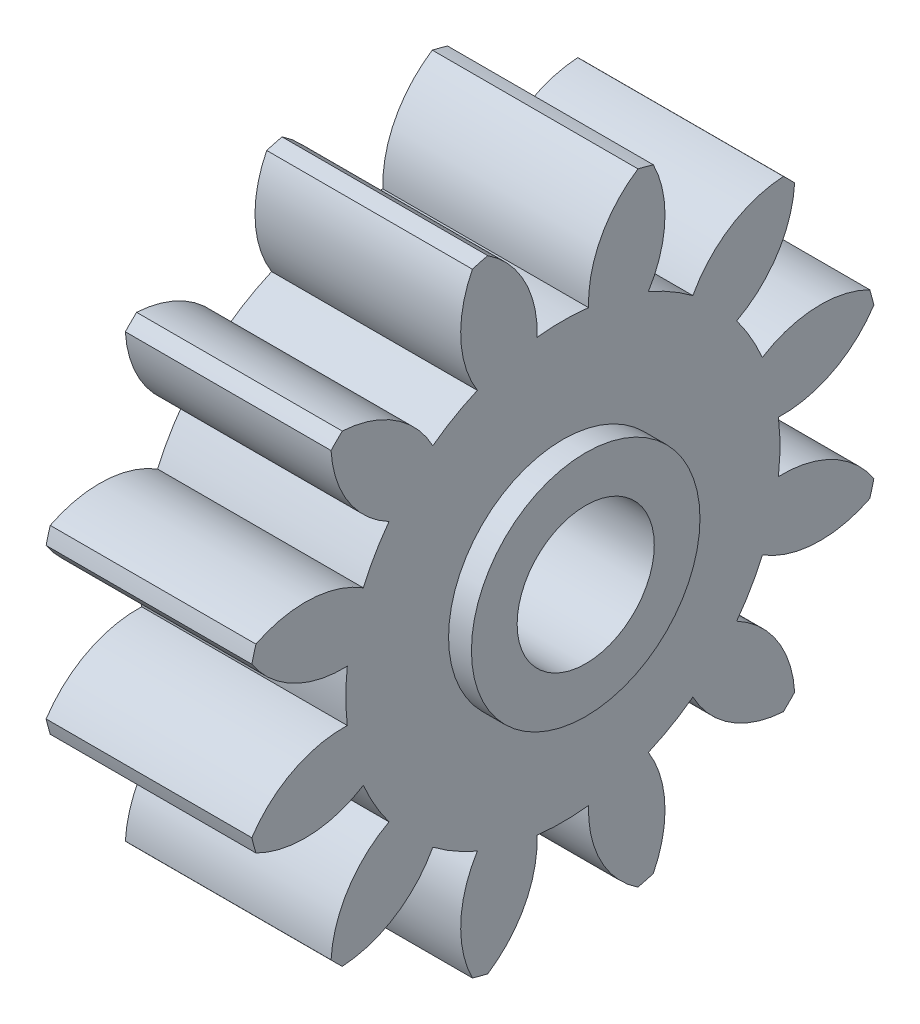
SolidWorks part; units mm, degrees
ref_plane "Plane1" through (0, 0, 0) normal (0, 0, 1) x (1, 0, 0)
ref_plane "Plane2" through (0, 0, 0) normal (0, 1, 0) x (1, 0, 0)
ref_plane "Plane3" through (0, 0, 0) normal (1, 0, 0) x (0, 0, -1)
sketch "HoldingSke" plane through (0, 0, 0) normal (0, 1, 0) x (1, 0, 0)
  line L0 (0, 0) -> (0.9781, -0.2079)
  line L1 (-15, 0) -> (100, 0) construction
  line L2 (0, 0) -> (-2.1039, 2.3779)
  line L3 (0, 0) -> (-11.863, 4.5341)
  line L4 (0, 0) -> (8.4473, 1.7955)
  line L5 (0, 0) -> (-5.1532, -1.922)
  line L6 (0, 0) -> (-3.7303, -2.5169)
  line L7 (-2.1039, 2.3779) -> (-0.92, 7.749)
  line L8 (-76.2, 54.61) -> (-75.7, 54.61)
  line L9 (-71.009, 38.7566) -> (-53.1078, 45.2721)
  line L10 (-76.2, 71.12) -> (104.1128, 71.12)
  line L11 (0, 0) -> (-4.5, 0)
  line L12 (-76.2, 101.6) -> (-76.162, 101.6)
  line L13 (24.9733, 27.94) -> (52.9518, 28.4284)
  line L14 (24.9733, 27.94) -> (24.9743, 27.94)
  line L15 (24.9733, 27.94) -> (100.4006, 29.5858)
  line L16 (-63.627, -1) -> (-12.827, -1)
  circle A0 centre (0, 0) radius 1.5
  circle A1 centre (0, 0) radius 2.5
  circle A2 centre (0, 0) radius 2.5
  circle A3 centre (0, 0) radius 1.5
  dimension "MHD" = 5
  dimension "Hub_dia" = 5
  dimension "Bore" = 3
  dimension "MBD" = 3
  dimension "Num_teeth" = 12
  dimension "Pitch" = 1
  dimension "Overall_len" = 5.5
  dimension "Show_teeth" = 12
  dimension "Thickness" = 4.5
  dimension "OAL" = 5.5001
  dimension "T_dim" = 0.5
  dimension "Ap" = 20
  dimension "H" = 19.05
  dimension "Pitch_radius" = 180.3128
  dimension "Width" = 4.5
  dimension "Backlash" = 0.038
  dimension "Addendum_fac" = 1
  dimension "Dedendum_fac" = 1.25
  dimension "Clearance_fac" = 0.25
  dimension "Dedendum_add" = 0.001
  dimension "Module" = 1
sketch "BasProSke" plane through (0, 0, 0) normal (0, 1, 0) x (1, 0, 0)
  line L0 (-10, 0) -> (60, 0) construction
  line L1 (0, 0) -> (0, 7)
  line L2 (0, 0) -> (4.5, 0)
  line L3 (4.5, 0) -> (4.5, 7)
  line L4 (4.5, 7) -> (0, 7)
  dimension "Thickness" = 4.5
  dimension "Diameter" = 14
revolve "Base-Revolve" add sketch "BasProSke" angle 360 about L0
sketch "TooCutSke" plane through (0, 0, 0) normal (1, 0, 0) x (0, 0, -1)
  line L1 (0, 0) -> (0, 107) construction
  line L2 (0, 0) -> (-0.8496, 5.9395) construction
  line L3 (0, 0) -> (-3.0836, 11.5081) construction
  line L4 (-0.8496, 5.9395) -> (-1.5418, 5.7541) construction
  arc A0 (0.5622, 4.7156) -> (-0.5622, 4.7156) centre (0, 0) ccw
  arc A1 (1.6729, 6.8233) -> (-1.6729, 6.8233) centre (0, 0) ccw
  circle A2 centre (0, 0) radius 6 construction
  circle A3 centre (0, 0) radius 5.6382 construction
  arc A4 (-0.5622, 4.7156) -> (-1.6729, 6.8233) centre (-2.9608, 4.7982) ccw
  arc A5 (1.6729, 6.8233) -> (0.5622, 4.7156) centre (2.9608, 4.7982) ccw
  dimension "Root_dia" = 9.498
  dimension "Overcut_dia" = 14.0508
  dimension "Pitch_dia" = 12
  dimension "Base_dia" = 11.2763
  dimension "Flank_rad" = 2.4
  dimension "Half_ang" = 15
  dimension "Half_CT" = 0.7167
extrude "ToothCut" cut sketch "TooCutSke" along normal through all
fillet "Breaks" [suppressed] radius 0.02
fillet "RootFillets" [suppressed] radius 0.251
pattern_circular "TeethCuts" count 12 every 30 about axis through (-10, 0, 0) along (1, 0, 0) of "ToothCut", "RootFillets", "Breaks"
sketch "HubNeaOneSke" plane through (0, 0, 0) normal (-1, 0, 0) x (0, 0, 1)
  circle A0 centre (0, 0) radius 2.5
  dimension "Diameter" = 5
extrude "HubNearOne" [suppressed] add sketch "HubNeaOneSke" along normal blind 1.0001
sketch "HubNeaBotSke" plane through (0, 0, 0) normal (-1, 0, 0) x (0, 0, 1)
  circle A0 centre (0, 0) radius 2.5
  dimension "Diameter" = 5
extrude "HubNearBoth" add sketch "HubNeaBotSke" along normal blind 0.5
ref_plane "FarPln" through (4.5, 0, 0) normal (1, 0, 0) x (0, 0, -1)
sketch "HubFarSke" plane through (4.5, 0, 0) normal (1, 0, 0) x (0, 0, -1)
  circle A0 centre (0, 0) radius 2.5
  dimension "Diameter" = 5
extrude "HubFar" add sketch "HubFarSke" along normal blind 0.5
sketch "BorSke" plane through (0, 0, 0) normal (1, 0, 0) x (0, 0, -1)
  circle A0 centre (0, 0) radius 1.5
  dimension "Diameter" = 3
extrude "Bore" cut sketch "BorSke" along normal mid plane 11.0001
sketch "KeySke" plane through (0, 0, 0) normal (1, 0, 0) x (0, 0, -1)
  line L0 (-0.6, 0) -> (-0.6, 2)
  line L1 (-0.6, 2) -> (0.6, 2)
  line L2 (0.6, 2) -> (0.6, 0)
  line L3 (0, 0) -> (0, 34) construction
  line L4 (-0.6, 0) -> (0.6, 0)
  dimension "Offset" = 2
  dimension "Width" = 1.2
extrude "Keyway" [suppressed] cut sketch "KeySke" along normal mid plane 11.0001
pattern_circular "Keyway2" [suppressed] count 2 every 90 about axis through (-10, 0, 0) along (1, 0, 0)
equation "' \"Module@HoldingSke\" = 6.35"
equation "' \"Num_teeth@HoldingSke\" = 12"
equation "' \"Ap@HoldingSke\" =  20"
equation "' \"Ap@HoldingSke\" = 20"
equation "' \"Width@HoldingSke\" = 0.5 * 25.4"
equation "' \"Hub_dia@HoldingSke\"= 1 * 25.4"
equation "' \"Hub_dia@HoldingSke\" = 1 * 25.4"
equation "' \"Overall_len@HoldingSke\" = 1.0 * 25.4"
equation "' \"Bore@HoldingSke\" = 0.75 * 25.4"
equation "' \"T_dim@HoldingSke\" = 0.1 * 25.4"
equation "' \"Width@KeySke\" = 0.25 * 25.4"
equation "' \"Show_teeth@HoldingSke\" = 13"
equation "' \"Backlash@HoldingSke\" = 0.009 * 25.4"
equation "' \"Addendum_fac@HoldingSke\" = 1.0"
equation "' \"Dedendum_fac@HoldingSke\" = 1.25"
equation "' \"Dedendum_add@HoldingSke\" = 0.00005 * 25.4"
equation "' \"Clearance_fac@HoldingSke\" = 0.25"
equation "\"Pitch@HoldingSke\" = 1 / \"Module@HoldingSke\""
equation "\"Overcut_dia@TooCutSke\" = (\"Num_teeth@HoldingSke\" + 2 * \"Addendum_fac@HoldingSke\") / \"Pitch@HoldingSke\" + 0.002 * 25.4"
equation "\"Pitch_dia@TooCutSke\" = \"Num_teeth@HoldingSke\" / \"Pitch@HoldingSke\""
equation "\"Base_dia@TooCutSke\" = \"Num_teeth@HoldingSke\" / \"Pitch@HoldingSke\" * cos((\"Ap@HoldingSke\"  * 3.14159265 / 180))"
equation "\"Root_dia@TooCutSke\" = (\"Num_teeth@HoldingSke\" + 2) / \"Pitch@HoldingSke\" - 2 * (\"Addendum_fac@HoldingSke\" + \"Dedendum_fac@HoldingSke\") / \"Pitch@HoldingSke\" - \"Dedendum_add@HoldingSke\" * 2"
equation "\"Half_ang@TooCutSke\" = 180 / \"Num_teeth@HoldingSke\""
equation "\"Half_CT@TooCutSke\" = \"Num_teeth@HoldingSke\" / \"Pitch@HoldingSke\" * sin((3.14159265 / 2 / \"Num_teeth@HoldingSke\")) / 2 - 7 * \"Backlash@HoldingSke\" / 4"
equation "\"Flank_rad@TooCutSke\" = \"Num_teeth@HoldingSke\" / \"Pitch@HoldingSke\" / 5"
equation "\"Radius@RootFillets\" = \"Clearance_fac@HoldingSke\" / \"Pitch@HoldingSke\" + \"Dedendum_add@HoldingSke\""
equation "\"Break_rad@Breaks\" = 0.02 / \"Pitch@HoldingSke\""
equation "\"Thickness@HoldingSke\" = \"Width@HoldingSke\""
equation "\"OAL@HoldingSke\" = \"Thickness@HoldingSke\""
equation "\"MHD@HoldingSke\" = (\"Num_teeth@HoldingSke\" + 2) / \"Pitch@HoldingSke\" - 2 * (\"Addendum_fac@HoldingSke\" + \"Dedendum_fac@HoldingSke\")  / \"Pitch@HoldingSke\" - \"Dedendum_add@HoldingSke\" * 2"
equation "\"MBD@HoldingSke\" = (\"Num_teeth@HoldingSke\" + 2) / \"Pitch@HoldingSke\" - 2 * (\"Addendum_fac@HoldingSke\" + \"Dedendum_fac@HoldingSke\")  / \"Pitch@HoldingSke\" - \"Dedendum_add@HoldingSke\" * 2 - 0.002 * 25.4"
equation "\"MHD@HoldingSke\" = ((sgn( \"MHD@HoldingSke\" - \"Hub_dia@HoldingSke\" )-1)*( \"MHD@HoldingSke\" - \"Hub_dia@HoldingSke\" ))/-2+ \"Hub_dia@HoldingSke\""
equation "\"MBD@HoldingSke\" = ((sgn( \"MBD@HoldingSke\" - \"Bore@HoldingSke\" )-1)*( \"MBD@HoldingSke\" - \"Bore@HoldingSke\" ))/-2+ \"Bore@HoldingSke\""
equation "\"OAL@HoldingSke\" = ((sgn( \"OAL@HoldingSke\" - \"Overall_len@HoldingSke\" )+1)*( \"OAL@HoldingSke\" - \"Overall_len@HoldingSke\" ))/2 + \"Overall_len@HoldingSke\" + 0.000002 * 25.4"
equation "\"Num_teeth@TeethCuts\" = int( \"Show_teeth@HoldingSke\" ) + 1"
equation "\"Num_teeth@TeethCuts\" = ((sgn( \"Num_teeth@TeethCuts\" - \"Num_teeth@HoldingSke\" )-1)*( \"Num_teeth@TeethCuts\" - \"Num_teeth@HoldingSke\" ))/-2+ \"Num_teeth@HoldingSke\""
equation "\"Num_teeth@TeethCuts\" = ((sgn( \"Num_teeth@TeethCuts\" - 2.0)+1)*( \"Num_teeth@TeethCuts\" - 2.0))/2 +2.0"
equation "\"Angle@TeethCuts\" = 360.0 / \"Num_teeth@HoldingSke\""
equation "\"Diameter@BasProSke\" = (\"Num_teeth@HoldingSke\" + 2 * \"Addendum_fac@HoldingSke\") / \"Pitch@HoldingSke\""
equation "\"Thickness@BasProSke\"  = \"Thickness@HoldingSke\""
equation "' \"Fillet_rad@BasProSke\" =  \"Thickness@HoldingSke\" * 0.05"
equation "' \"Fillet_rad@BasProSke\" = \"Thickness@HoldingSke\" * 0.05"
equation "\"MHD@HoldingSke\" = ((sgn( \"MHD@HoldingSke\" - \"Root_dia@TooCutSke\" )-1)*( \"MHD@HoldingSke\" - \"Root_dia@TooCutSke\" ))/-2+ \"Root_dia@TooCutSke\""
equation "\"Diameter@HubNeaOneSke\" = \"MHD@HoldingSke\""
equation "\"Length@HubNearOne\" = \"OAL@HoldingSke\" - \"Thickness@BasProSke\""
equation "\"Diameter@HubNeaBotSke\" = \"MHD@HoldingSke\""
equation "\"Length@HubNearBoth\" = ( \"OAL@HoldingSke\" - \"Thickness@BasProSke\" ) / 2.0"
equation "\"Thickness@FarPln\" = \"Thickness@BasProSke\""
equation "\"Diameter@HubFarSke\" = \"MHD@HoldingSke\""
equation "\"Length@HubFar\" = ( \"OAL@HoldingSke\" - \"Thickness@BasProSke\" ) / 2.0"
equation "\"Diameter@BorSke\" = \"MBD@HoldingSke\""
equation "\"D1@Bore\" = \"OAL@HoldingSke\" * 2.0"
equation "\"D1@Keyway\" = \"OAL@HoldingSke\" * 2.0"
equation "\"Offset@KeySke\" = \"T_dim@HoldingSke\" + \"MBD@HoldingSke\" / 2.0"
